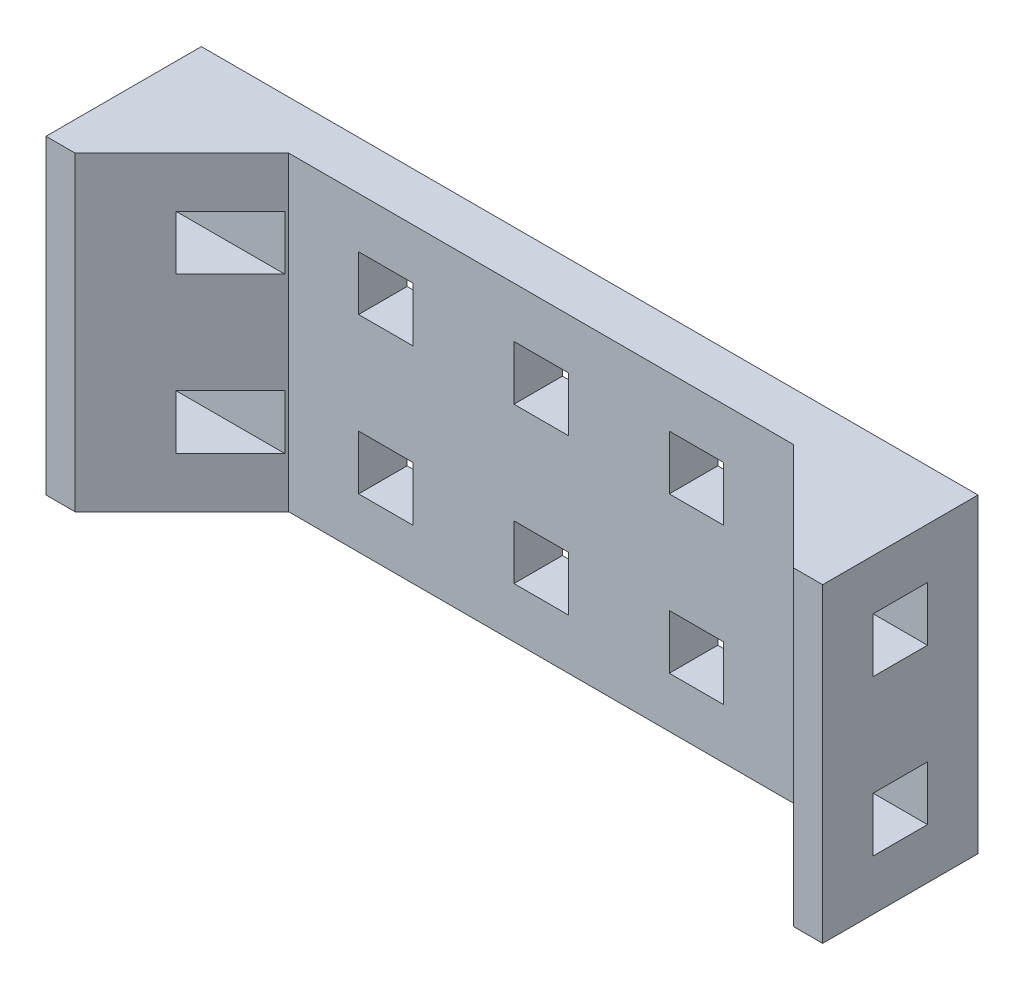
SolidWorks part; units mm, degrees
ref_plane "Plano frontal" through (0, 0, 0) normal (0, 0, 1) x (1, 0, 0)
ref_plane "Plano superior" through (0, 0, 0) normal (0, 1, 0) x (1, 0, 0)
ref_plane "Plano direito" through (0, 0, 0) normal (1, 0, 0) x (0, 0, -1)
sketch "Esboço1" plane through (0, 0, 0) normal (0, 0, 1) x (1, 0, 0)
  line L0 (-25, 0) -> (25, 0)
  line L1 (25, 0) -> (25, 8)
  line L2 (25, 8) -> (23.5, 8)
  line L3 (23.5, 8) -> (18, 2.5)
  line L4 (18, 2.5) -> (-18, 2.5)
  line L5 (0, 0) -> (0, 2.5) construction
  line L6 (-23.5, 8) -> (-18, 2.5)
  line L7 (-25, 8) -> (-23.5, 8)
  line L8 (-25, 0) -> (-25, 8)
  dimension "D1" = 45
  dimension "D2" = 2.5
  dimension "D3" = 1.5
  dimension "D4" = 8
extrude "Ressalto-extrusão1" add sketch "Esboço1" along normal blind 16
sketch "Esboço2" plane through (25, 0, 0) normal (1, 0, 0) x (0, 0, -1)
  line L0 (-8, 0) -> (-8, 4) construction
  line L1 (-16, 0) -> (0, 0) construction
  line L2 (-8, 4) -> (-4, 4) construction
  line L3 (-8, 4) -> (-12, 4) construction
  line L4 (-5.4, 5.4) -> (-5.4, 2.6)
  line L5 (-13.4, 5.4) -> (-10.6, 5.4)
  line L6 (-13.4, 5.4) -> (-13.4, 2.6)
  line L7 (-13.4, 2.6) -> (-10.6, 2.6)
  line L8 (-10.6, 5.4) -> (-10.6, 2.6)
  line L9 (-13.4, 5.4) -> (-10.6, 2.6) construction
  line L10 (-13.4, 2.6) -> (-10.6, 5.4) construction
  line L11 (-5.4, 5.4) -> (-2.6, 5.4)
  line L12 (-5.4, 5.4) -> (-2.6, 2.6) construction
  line L13 (-5.4, 2.6) -> (-2.6, 2.6)
  line L14 (-2.6, 5.4) -> (-2.6, 2.6)
  line L15 (-5.4, 2.6) -> (-2.6, 5.4) construction
extrude "Corte-extrusão1" cut sketch "Esboço2" against normal through all
sketch "Esboço3" plane through (0, 2.5, 0) normal (0, 1, 0) x (1, 0, 0)
  line L0 (0, 0) -> (0, -16) construction
  line L1 (18, -16) -> (-18, -16) construction
  line L3 (-14, -3) -> (14, -3)
  line L4 (-14, -3) -> (-14, -13)
  line L5 (-14, -13) -> (14, -13)
  line L6 (14, -3) -> (14, -13)
  line L7 (-14, -3) -> (14, -13) construction
  line L8 (-14, -13) -> (14, -3) construction
  point P5 (0, -8)
sketch "Esboço4" plane through (0, 2.5, 0) normal (0, 1, 0) x (1, 0, 0)
  line L0 (0, -8) -> (-16, -8) construction
  line L1 (-16, -8) -> (-16, -4) construction
  line L2 (-9.4, -2.6) -> (-6.6, -5.4) construction
  line L3 (-17.4, -2.6) -> (-14.6, -2.6)
  line L4 (-17.4, -2.6) -> (-17.4, -5.4)
  line L5 (-17.4, -5.4) -> (-14.6, -5.4)
  line L6 (-14.6, -2.6) -> (-14.6, -5.4)
  line L7 (-17.4, -2.6) -> (-14.6, -5.4) construction
  line L8 (-17.4, -5.4) -> (-14.6, -2.6) construction
  line L9 (-9.4, -5.4) -> (-6.6, -2.6) construction
  line L10 (-9.4, -2.6) -> (-9.4, -5.4)
  line L11 (-9.4, -2.6) -> (-6.6, -2.6)
  line L12 (-6.6, -2.6) -> (-6.6, -5.4)
  line L13 (-9.4, -5.4) -> (-6.6, -5.4)
  line L14 (-1.4, -2.6) -> (1.4, -5.4) construction
  line L15 (-1.4, -5.4) -> (1.4, -2.6) construction
  line L16 (-1.4, -2.6) -> (-1.4, -5.4)
  line L17 (-1.4, -2.6) -> (1.4, -2.6)
  line L18 (1.4, -2.6) -> (1.4, -5.4)
  line L19 (-1.4, -5.4) -> (1.4, -5.4)
  line L20 (6.6, -2.6) -> (9.4, -5.4) construction
  line L21 (6.6, -5.4) -> (9.4, -2.6) construction
  line L22 (6.6, -2.6) -> (6.6, -5.4)
  line L23 (6.6, -2.6) -> (9.4, -2.6)
  line L24 (9.4, -2.6) -> (9.4, -5.4)
  line L25 (6.6, -5.4) -> (9.4, -5.4)
  line L26 (14.6, -2.6) -> (17.4, -5.4) construction
  line L27 (14.6, -5.4) -> (17.4, -2.6) construction
  line L28 (14.6, -2.6) -> (14.6, -5.4)
  line L29 (14.6, -2.6) -> (17.4, -2.6)
  line L30 (17.4, -2.6) -> (17.4, -5.4)
  line L31 (14.6, -5.4) -> (17.4, -5.4)
  line L32 (-9.4, -10.6) -> (-6.6, -13.4) construction
  line L33 (-9.4, -13.4) -> (-6.6, -10.6) construction
  line L34 (-9.4, -10.6) -> (-9.4, -13.4)
  line L35 (-9.4, -10.6) -> (-6.6, -10.6)
  line L36 (-6.6, -10.6) -> (-6.6, -13.4)
  line L37 (-9.4, -13.4) -> (-6.6, -13.4)
  line L38 (-1.4, -10.6) -> (1.4, -13.4) construction
  line L39 (-1.4, -13.4) -> (1.4, -10.6) construction
  line L40 (-1.4, -10.6) -> (-1.4, -13.4)
  line L41 (-1.4, -10.6) -> (1.4, -10.6)
  line L42 (1.4, -10.6) -> (1.4, -13.4)
  line L43 (-1.4, -13.4) -> (1.4, -13.4)
  line L44 (6.6, -10.6) -> (9.4, -13.4) construction
  line L45 (6.6, -13.4) -> (9.4, -10.6) construction
  line L46 (6.6, -10.6) -> (6.6, -13.4)
  line L47 (6.6, -10.6) -> (9.4, -10.6)
  line L48 (9.4, -10.6) -> (9.4, -13.4)
  line L49 (6.6, -13.4) -> (9.4, -13.4)
  line L50 (14.6, -10.6) -> (17.4, -13.4) construction
  line L51 (14.6, -13.4) -> (17.4, -10.6) construction
  line L52 (14.6, -10.6) -> (14.6, -13.4)
  line L53 (14.6, -10.6) -> (17.4, -10.6)
  line L54 (17.4, -10.6) -> (17.4, -13.4)
  line L55 (14.6, -13.4) -> (17.4, -13.4)
  line L56 (-17.4, -10.6) -> (-14.6, -13.4) construction
  line L57 (-17.4, -13.4) -> (-14.6, -10.6) construction
  line L58 (-17.4, -10.6) -> (-17.4, -13.4)
  line L59 (-17.4, -10.6) -> (-14.6, -10.6)
  line L60 (-14.6, -10.6) -> (-14.6, -13.4)
  line L61 (-17.4, -13.4) -> (-14.6, -13.4)
  dimension "D1" = 5
  dimension "D2" = 2
extrude "Corte-extrusão2" cut sketch "Esboço4" against normal through all
move or copy body "Corpo-Mover/Copiar1" bodies to move or copy 104 copy no rotation origin (0, 4, 8) rotation axis (1, 0, 0) rotation angle 90
sketch "Esboço6" plane through (0, 0, 4) normal (0, 0, -1) x (-1, 0, 0)
  line L1 (25, -4) -> (-25, -4) construction
  line L2 (5, -4) -> (5, 12)
  line L3 (25, 12) -> (-25, 12) construction
  line L4 (5, 12) -> (-25, 12)
  line L5 (-25, 12) -> (-25, -4)
  line L6 (5, -4) -> (-25, -4)
extrude "Corte-extrusão3" cut sketch "Esboço6" against normal through all
mirror "Espelhar3" about plane through (-5, -4, 12) normal (-1, 0, 0) of bodies 106
sketch "Esboço7" plane through (0, 0, 6.5) normal (0, 0, 1) x (1, 0, 0)
  line L1 (-17.582, 9.9145) -> (7.6394, 9.9145)
  line L2 (-17.582, 9.9145) -> (-17.582, -2.6616)
  line L3 (-17.582, -2.6616) -> (7.6394, -2.6616)
  line L4 (7.6394, 9.9145) -> (7.6394, -2.6616)
extrude "Ressalto-extrusão2" add sketch "Esboço7" against normal through all
sketch "Esboço8" plane through (0, 0, 6.5) normal (0, 0, 1) x (1, 0, 0)
  line L0 (-5, -4) -> (-5, 12) construction
  line L1 (8, -4) -> (-18, -4) construction
  line L2 (8, 12) -> (-18, 12) construction
  line L3 (-5, 4) -> (-5, 8) construction
  line L4 (-5, 8) -> (-13, 8) construction
  line L5 (-6.4, 9.4) -> (-3.6, 9.4)
  line L6 (-14.4, 9.4) -> (-11.6, 9.4)
  line L7 (-14.4, 9.4) -> (-14.4, 6.6)
  line L8 (-14.4, 6.6) -> (-11.6, 6.6)
  line L9 (-11.6, 9.4) -> (-11.6, 6.6)
  line L10 (-14.4, 9.4) -> (-11.6, 6.6) construction
  line L11 (-14.4, 6.6) -> (-11.6, 9.4) construction
  line L12 (-6.4, 9.4) -> (-6.4, 6.6)
  line L13 (-6.4, 6.6) -> (-3.6, 6.6)
  line L14 (-3.6, 9.4) -> (-3.6, 6.6)
  line L15 (-6.4, 9.4) -> (-3.6, 6.6) construction
  line L16 (-6.4, 6.6) -> (-3.6, 9.4) construction
  line L17 (1.6, 9.4) -> (4.4, 9.4)
  line L18 (1.6, 9.4) -> (1.6, 6.6)
  line L19 (1.6, 6.6) -> (4.4, 6.6)
  line L20 (4.4, 9.4) -> (4.4, 6.6)
  line L21 (1.6, 9.4) -> (4.4, 6.6) construction
  line L22 (1.6, 6.6) -> (4.4, 9.4) construction
  line L23 (-6.4, 1.4) -> (-3.6, 1.4)
  line L24 (-6.4, 1.4) -> (-6.4, -1.4)
  line L25 (-6.4, -1.4) -> (-3.6, -1.4)
  line L26 (-3.6, 1.4) -> (-3.6, -1.4)
  line L27 (-6.4, 1.4) -> (-3.6, -1.4) construction
  line L28 (-6.4, -1.4) -> (-3.6, 1.4) construction
  line L29 (1.6, 1.4) -> (4.4, 1.4)
  line L30 (1.6, 1.4) -> (1.6, -1.4)
  line L31 (1.6, -1.4) -> (4.4, -1.4)
  line L32 (4.4, 1.4) -> (4.4, -1.4)
  line L33 (1.6, 1.4) -> (4.4, -1.4) construction
  line L34 (1.6, -1.4) -> (4.4, 1.4) construction
  line L35 (-14.4, 1.4) -> (-11.6, 1.4)
  line L36 (-14.4, 1.4) -> (-14.4, -1.4)
  line L37 (-14.4, -1.4) -> (-11.6, -1.4)
  line L38 (-11.6, 1.4) -> (-11.6, -1.4)
  line L39 (-14.4, 1.4) -> (-11.6, -1.4) construction
  line L40 (-14.4, -1.4) -> (-11.6, 1.4) construction
  dimension "D1" = 4
  dimension "D2" = 8
  dimension "D3" = 2.8
  dimension "D4" = 3
  dimension "D5" = 2
extrude "Corte-extrusão4" cut sketch "Esboço8" against normal through all
